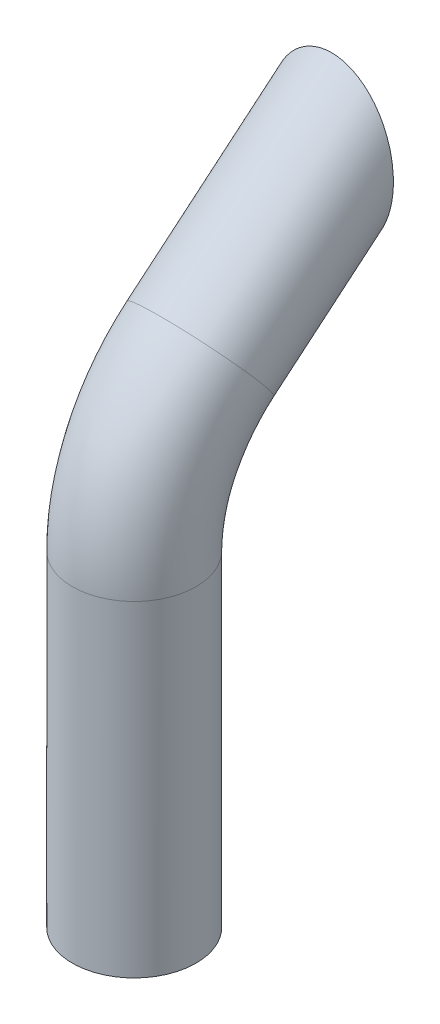
SolidWorks part; units mm, degrees
ref_plane "Front Plane" through (0, 0, 0) normal (0, 0, 1) x (1, 0, 0)
ref_plane "Top Plane" through (0, 0, 0) normal (0, 1, 0) x (1, 0, 0)
ref_plane "Right Plane" through (0, 0, 0) normal (1, 0, 0) x (0, 0, -1)
sketch "Sketch1" plane through (0, 0, 0) normal (1, 0, 0) x (0, 0, -1)
  line L0 (0, 0) -> (-82.7576, -69.4418)
  line L1 (-114.9067, -138.3858) -> (-114.9067, -296.4181)
  arc A0 (-82.7576, -69.4418) -> (-114.9067, -138.3858) centre (-24.9067, -138.3858) ccw
  point P6 (-114.9067, -96.4181)
  dimension "D4" = 90
  dimension "D1" = 150
  dimension "D2" = 200
  dimension "D3" = 130
ref_plane "Plane1" through (0, 0, 0) normal (0, -0.6428, 0.766) x (1, 0, 0)
sketch "Sketch2" plane through (0, 0, 0) normal (0, -0.6428, 0.766) x (1, 0, 0)
  circle A0 centre (0, 0) radius 30
  dimension "D1" = 60
sweep "Sweep-Thin1" add profiles "Sketch2" path "Sketch1" parameters "D1"=3
sketch "Sketch3" plane through (0, 0, 0) normal (1, 0, 0) x (0, 0, -1)
  line L1 (-19.2836, 22.9813) -> (72.3759, 22.9813)
  line L2 (-19.2836, 22.9813) -> (-19.2836, -61.8965)
  line L3 (-19.2836, -61.8965) -> (72.3759, -61.8965)
  line L4 (72.3759, 22.9813) -> (72.3759, -61.8965)
extrude "Cut-Extrude1" cut sketch "Sketch3" against normal mid plane 100
